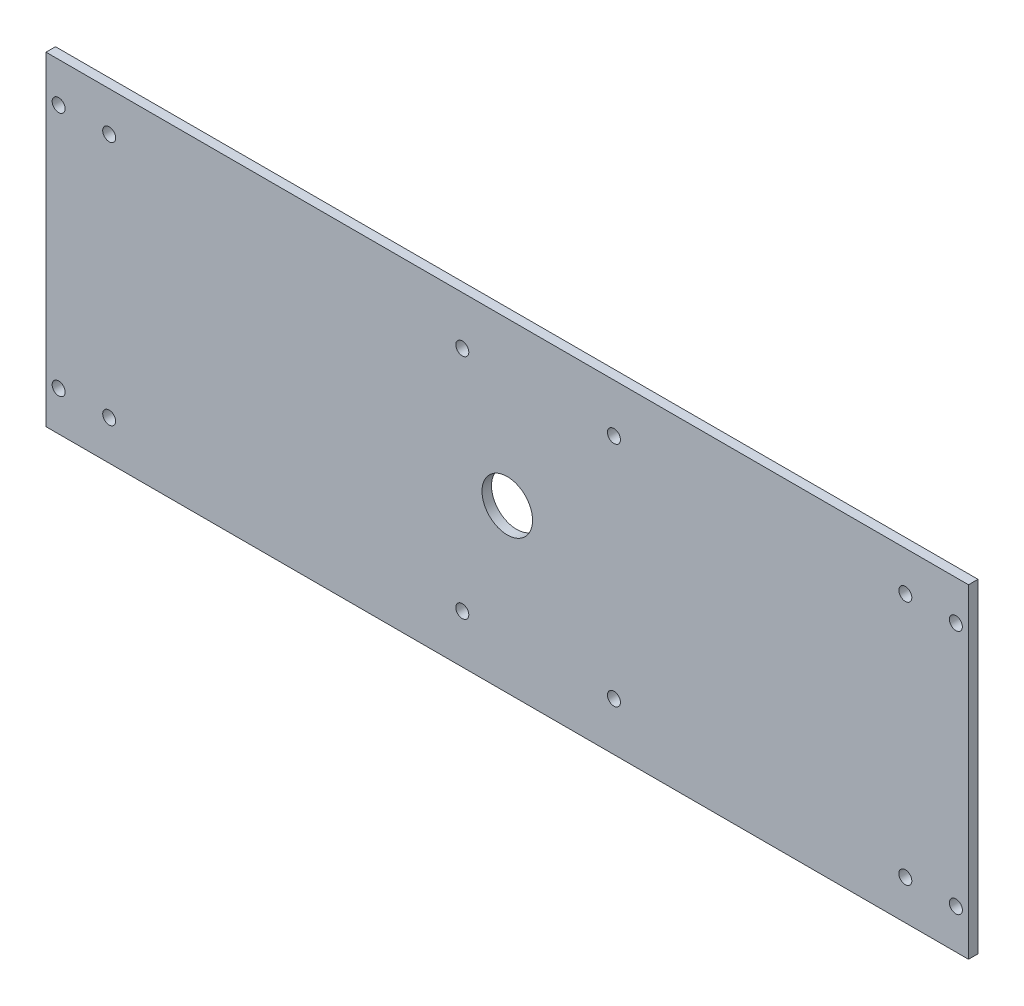
SolidWorks part; units mm, degrees
material "E-Glass Fiber"
ref_plane "Front Plane" through (0, 0, 0) normal (0, 0, 1) x (1, 0, 0)
ref_plane "Top Plane" through (0, 0, 0) normal (0, 1, 0) x (1, 0, 0)
ref_plane "Right Plane" through (0, 0, 0) normal (1, 0, 0) x (0, 0, -1)
sketch "Sketch1" plane through (0, 0, 0) normal (0, 0, 1) x (1, 0, 0)
  line L1 (-115.8875, -40.748) -> (115.8875, -40.748)
  line L2 (-115.8875, -40.748) -> (-115.8875, 40.7479)
  line L3 (-115.8875, 40.7479) -> (115.8875, 40.7479)
  line L4 (115.8875, -40.748) -> (115.8875, 40.7479)
  line L5 (-115.8875, -40.748) -> (115.8875, 40.7479) construction
  line L6 (-115.8875, 40.7479) -> (115.8875, -40.748) construction
  point P0 (0, 0)
  dimension "D1" = 231.775
  dimension "D2" = 81.4959
extrude "Boss-Extrude1" add sketch "Sketch1" along normal blind 2.3813
sketch "Sketch2" plane through (0, 0, 2.3813) normal (0, 0, 1) x (1, 0, 0)
  line L0 (-11.2979, 28.575) -> (26.8021, 28.575) construction
  line L1 (-115.8875, 0) -> (-111.125, 0) construction
  line L3 (-115.8875, 40.7479) -> (-115.8875, -40.748) construction
  line L4 (-111.125, 0) -> (-111.125, 9.525) construction
  line L5 (-111.125, 9.525) -> (-111.125, 25.4) construction
  line L6 (115.8875, 0) -> (111.125, 0) construction
  line L7 (115.8875, -40.748) -> (115.8875, 40.7479) construction
  line L8 (111.125, 0) -> (111.125, 9.525) construction
  line L9 (111.125, 9.525) -> (111.125, 25.4) construction
  line L10 (-112.7125, 40.7479) -> (-112.7125, 30.8204) construction
  line L11 (115.8875, 40.7479) -> (-115.8875, 40.7479) construction
  line L12 (-112.7125, 30.8204) -> (-100.0125, 30.8204) construction
  line L13 (-112.7125, 30.8204) -> (-115.8875, 30.8204) construction
  dimension "D1" = 38.1
  dimension "D2" = 28.575
  dimension "D3" = 11.2979
  dimension "D4" = 9.525
  dimension "D5" = 25.4
  dimension "D6" = 4.7625
  dimension "D7" = 3.175
  dimension "D8" = 30.8204
  dimension "D9" = 12.7
hole_wizard "#4 Clearance Hole1" positions "Sketch4" profile "Sketch5" hole size "#4" standard "ANSI Inch" end condition through all
sketch "Sketch4" plane through (0, 0, 2.3813) normal (0, 0, 1) x (1, 0, 0)
  point P0 (-11.2979, 28.575)
  point P3 (26.8021, 28.575)
sketch "Sketch5" plane through (-11.2979, 28.575, 2.3813) normal (1, 0, 0) x (0, -1, 0)
  line L0 (0, 0) -> (0, 2.3813)
  line L1 (0, 2.3813) -> (1.6319, 2.3813)
  line L2 (1.6319, 2.3813) -> (1.6319, 0)
  line L5 (1.6319, 0) -> (0, 0)
  line L11 (0, -6.35) -> (0, 107.95) construction
  dimension "Thru Hole Dia." = 3.2639
  dimension "Thru Hole Depth" = 2.3813
mirror "Mirror1" about plane through (0, 0, 0) normal (0, 1, 0) of "#4 Clearance Hole1"
hole_wizard "#4 Clearance Hole2" positions "Sketch7" profile "Sketch6" hole size "#4" standard "ANSI Inch"
sketch "Sketch7" plane through (0, 0, 2.3813) normal (0, 0, 1) x (1, 0, 0)
  point P0 (-112.7125, 30.8204)
  point P3 (-100.0125, 30.8204)
sketch "Sketch6" plane through (-112.7125, 30.8204, 2.3813) normal (1, 0, 0) x (0, -1, 0)
  line L0 (0, 0) -> (0, 10.5056)
  line L1 (0, 10.5056) -> (1.6319, 9.525)
  line L2 (1.6319, 9.525) -> (1.6319, 0)
  line L5 (1.6319, 0) -> (0, 0)
  line L10 (0, 10.5056) -> (-1.632, 9.525) construction
  line L11 (0, -6.35) -> (0, 107.95) construction
  dimension "Hole Dia." = 3.2639
  dimension "Hole Depth" = 9.525
  dimension "Drill Angle" = 118
mirror "Mirror2" about plane through (0, 0, 0) normal (1, 0, 0) of "#4 Clearance Hole2"
mirror "Mirror3" about plane through (0, 0, 0) normal (0, 1, 0) of "Mirror2", "#4 Clearance Hole2"
hole_wizard "1/2 (0.5) Diameter Hole1" positions "Sketch9" profile "Sketch8" hole size "1/2" standard "ANSI Inch" end condition through all
sketch "Sketch9" plane through (0, 0, 2.3813) normal (0, 0, 1) x (1, 0, 0)
  point P0 (0, 0)
sketch "Sketch8" plane through (0, 0, 2.3813) normal (1, 0, 0) x (0, -1, 0)
  line L0 (0, 0) -> (0, 2.3812)
  line L1 (0, 2.3812) -> (6.35, 2.3812)
  line L2 (6.35, 2.3812) -> (6.35, 0)
  line L5 (6.35, 0) -> (0, 0)
  line L11 (0, -6.35) -> (0, 107.95) construction
  dimension "Thru Hole Dia." = 12.7
  dimension "Thru Hole Depth" = 2.3813
